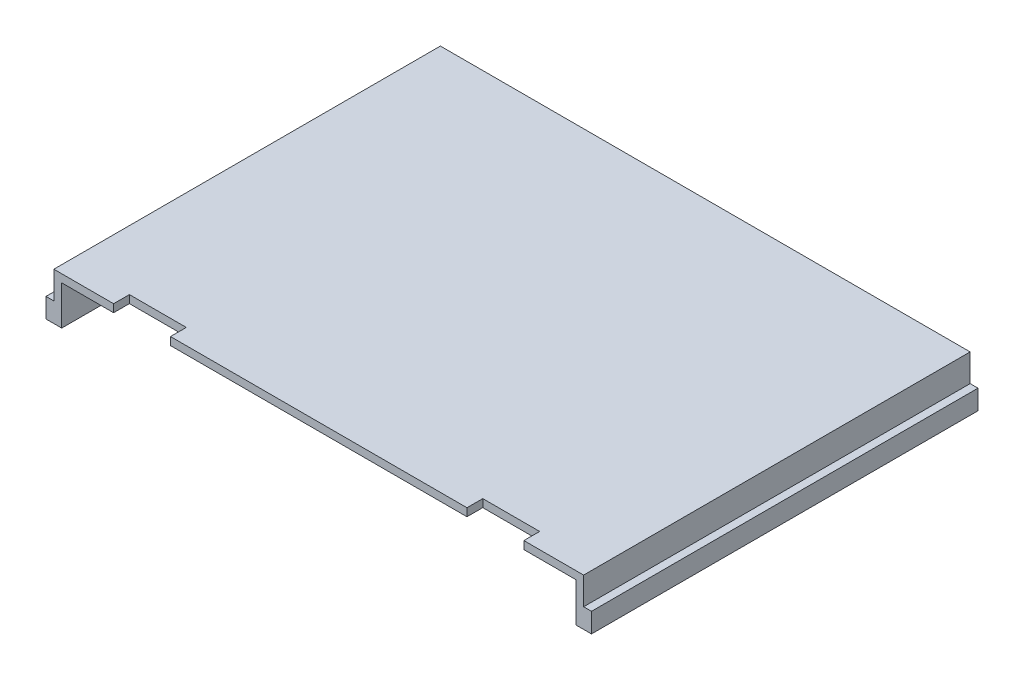
SolidWorks part; units mm, degrees
ref_plane "Alzado" through (0, 0, 0) normal (0, 0, 1) x (1, 0, 0)
ref_plane "Planta" through (0, 0, 0) normal (0, 1, 0) x (1, 0, 0)
ref_plane "Vista lateral" through (0, 0, 0) normal (1, 0, 0) x (0, 0, -1)
sketch "Croquis1" plane through (0, 0, 0) normal (0, 0, 1) x (1, 0, 0)
  line L1 (219.3659, 10.0122) -> (-50.6341, 10.0122)
  line L2 (-50.6341, 10.0122) -> (-50.6341, -3.9878)
  line L6 (-46.6341, -3.9878) -> (-46.6341, 6.0122)
  line L7 (-46.6341, 6.0122) -> (215.3659, 6.0122)
  line L8 (219.1358, -13.9878) -> (215.3659, -13.9878)
  line L9 (219.3659, 10.0122) -> (219.3659, -3.9878)
  line L10 (215.3659, -3.9878) -> (215.3659, 6.0122)
  line L13 (-46.6341, 1.0122) -> (-50.6341, 1.0122) construction
  line L14 (-50.6341, 1.0122) -> (-46.6341, 1.0122) construction
  line L15 (-20.5689, 10.0122) -> (-20.5689, 6.0122) construction
  line L16 (215.3659, 1.0122) -> (219.3659, 1.0122) construction
  line L17 (-50.6341, -3.9878) -> (-54.6341, -3.9878)
  line L18 (-54.6341, -3.9878) -> (-54.6341, -13.9878)
  line L19 (-54.6341, -13.9878) -> (-49.3449, -13.9878)
  line L20 (-46.6341, -3.9878) -> (-46.6341, -13.9878)
  line L21 (-46.6341, -13.9878) -> (-49.3449, -13.9878)
  line L22 (219.3659, -3.9878) -> (223.3659, -3.9878)
  line L23 (223.3659, -3.9878) -> (223.3659, -13.9878)
  line L24 (223.3659, -13.9878) -> (219.1358, -13.9878)
  line L25 (215.3659, -3.9878) -> (215.3659, -13.9878)
  dimension "D1" = 4
  dimension "D2" = 4
  dimension "D3" = 270
extrude "Saliente-Extruir1" add sketch "Croquis1" along normal blind 197
sketch "Croquis3" plane through (0, 10.0122, 0) normal (0, 1, 0) x (1, 0, 0)
  line L0 (219.3659, -197) -> (-50.6341, -197) construction
  line L1 (-50.6341, -197) -> (-50.6341, 0) construction
  line L2 (-20.1841, -197) -> (-20.1841, -188.95) construction
  line L3 (-20.1841, -188.95) -> (8.8159, -188.95) construction
  line L4 (8.8159, -188.95) -> (8.8159, -197) construction
  line L5 (8.8159, -197) -> (-20.1841, -197) construction
  line L6 (84.3659, 0) -> (84.3659, -197) construction
  line L7 (219.3659, 0) -> (-50.6341, 0) construction
  line L8 (159.9159, -188.95) -> (159.9159, -197) construction
  line L9 (159.9159, -197) -> (188.9159, -197) construction
  line L10 (188.9159, -197) -> (188.9159, -188.95) construction
  line L11 (188.9159, -188.95) -> (159.9159, -188.95) construction
  line L13 (-20.1841, -197) -> (8.8159, -197)
  line L14 (-20.1841, -197) -> (-20.1841, -188.95)
  line L15 (-20.1841, -188.95) -> (8.8159, -188.95)
  line L16 (8.8159, -197) -> (8.8159, -188.95)
  line L17 (159.9159, -197) -> (188.9159, -197)
  line L18 (159.9159, -197) -> (159.9159, -188.95)
  line L19 (159.9159, -188.95) -> (188.9159, -188.95)
  line L20 (188.9159, -197) -> (188.9159, -188.95)
  dimension "D1" = 30.45
  dimension "D2" = 8.05
  dimension "D3" = 29
extrude "Cortar-Extruir1" cut sketch "Croquis3" against normal through all
